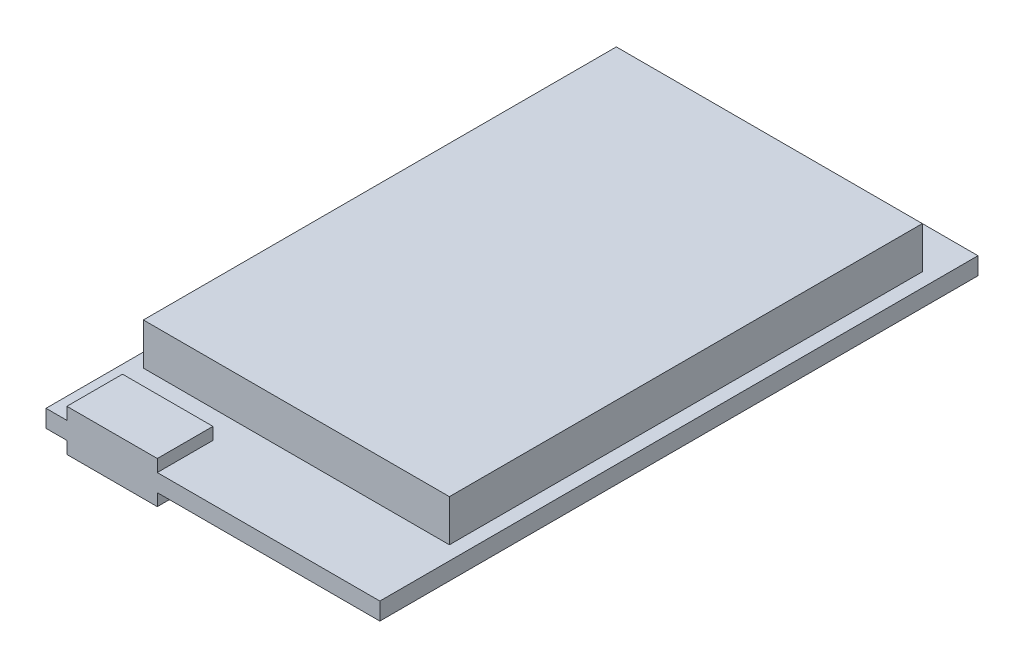
SolidWorks part; units mm, degrees
ref_plane "Front Plane" through (0, 0, 0) normal (0, 0, 1) x (1, 0, 0)
ref_plane "Top Plane" through (0, 0, 0) normal (0, 1, 0) x (1, 0, 0)
ref_plane "Right Plane" through (0, 0, 0) normal (1, 0, 0) x (0, 0, -1)
sketch "Sketch1" plane through (0, 0, 0) normal (0, 1, 0) x (1, 0, 0)
  line L1 (-12, 21.5) -> (12, 21.5)
  line L2 (-12, 21.5) -> (-12, -21.5)
  line L3 (-12, -21.5) -> (12, -21.5)
  line L4 (12, 21.5) -> (12, -21.5)
  line L5 (-12, 21.5) -> (12, -21.5) construction
  line L6 (-12, -21.5) -> (12, 21.5) construction
  point P0 (0, 0)
  dimension "D1" = 43
  dimension "D2" = 24
extrude "PCB" add sketch "Sketch1" along normal blind 1.25
sketch "Sketch2" plane through (0, 1.25, 0) normal (0, 1, 0) x (1, 0, 0)
  line L0 (-12, -21.5) -> (12, -21.5) construction
  line L1 (-11, 18.5) -> (11, 18.5)
  line L2 (-11, 18.5) -> (-11, -15.5)
  line L3 (-11, -15.5) -> (11, -15.5)
  line L4 (11, 18.5) -> (11, -15.5)
  line L5 (-11, 18.5) -> (11, -15.5) construction
  line L6 (-11, -15.5) -> (11, 18.5) construction
  point P0 (0, 1.5)
  dimension "D1" = 34
  dimension "D2" = 22
  dimension "D3" = 6
extrude "RF Casing" add sketch "Sketch2" along normal blind 3
sketch "Sketch5" plane through (0, 0, 21.5) normal (0, 0, 1) x (1, 0, 0)
  line L1 (-10.4992, 2.125) -> (-3.9992, 2.125)
  line L2 (-10.4992, 2.125) -> (-10.4992, -0.875)
  line L3 (-10.4992, -0.875) -> (-3.9992, -0.875)
  line L4 (-3.9992, 2.125) -> (-3.9992, -0.875)
  line L5 (-10.4992, 2.125) -> (-3.9992, -0.875) construction
  line L6 (-10.4992, -0.875) -> (-3.9992, 2.125) construction
  line L8 (-12, 1.25) -> (-12, 0) construction
  line L9 (-12, 1.25) -> (-12, 0) construction
  point P0 (-7.2492, 0.625)
  point P8 (0, 0)
  point P9 (-7.2492, 0.625)
  point P12 (-12, 0.625)
  dimension "D1" = 3
  dimension "D2" = 6.5
  dimension "D3" = 8.0008
extrude "Pins" add sketch "Sketch5" against normal blind 4
